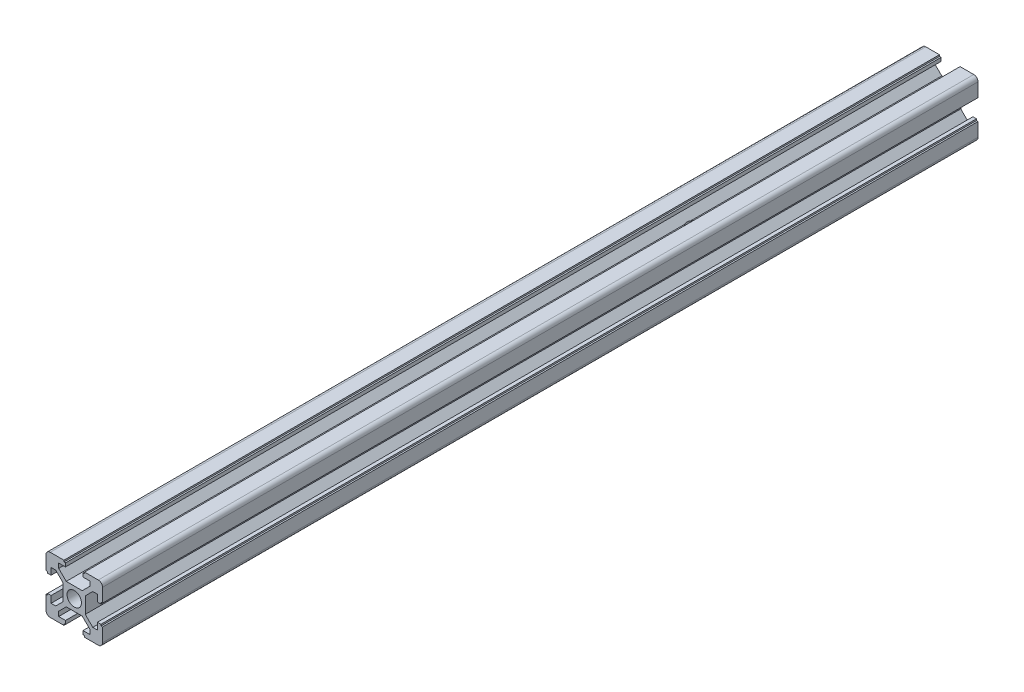
SolidWorks part; units mm, degrees
material "6063-T5"
ref_plane "前视基准面" through (0, 0, 0) normal (0, 0, 1) x (1, 0, 0)
ref_plane "上视基准面" through (0, 0, 0) normal (0, 1, 0) x (1, 0, 0)
ref_plane "右视基准面" through (0, 0, 0) normal (1, 0, 0) x (0, 0, -1)
sketch "草图2" plane through (0, 0, 0) normal (0, 0, 1) x (1, 0, 0)
  line L0 (-3.9, 2.8393) -> (-6.5607, 5.5)
  line L1 (-2.8393, 3.9) -> (2.8393, 3.9)
  line L2 (-3.9, 2.8393) -> (-3.9, -2.8393)
  line L3 (-2.8393, -3.9) -> (2.8393, -3.9)
  line L4 (3.9, 2.8393) -> (3.9, -2.8393)
  line L5 (-3.9, 3.9) -> (3.9, -3.9) construction
  line L6 (-3.9, -3.9) -> (3.9, 3.9) construction
  line L7 (-2.8393, 3.9) -> (-5.5, 6.5607)
  line L8 (-5.5, 6.5607) -> (-5.5, 8.2)
  line L9 (-5.5, 8.2) -> (-3.1, 8.2)
  line L10 (-3.1, 8.2) -> (-3.1, 9.45)
  line L11 (-3.1, 9.45) -> (-3.65, 9.45)
  line L12 (-3.65, 9.45) -> (-3.65, 10)
  line L13 (-3.65, 10) -> (-8.5, 10)
  line L14 (-6.5607, 5.5) -> (-8.2, 5.5)
  line L15 (-10, 3.65) -> (-10, 8.5)
  line L16 (-9.45, 3.65) -> (-10, 3.65)
  line L17 (-9.45, 3.1) -> (-9.45, 3.65)
  line L18 (-8.2, 3.1) -> (-9.45, 3.1)
  line L19 (-8.2, 5.5) -> (-8.2, 3.1)
  line L20 (2.8393, 3.9) -> (5.5, 6.5607)
  line L21 (3.9, 2.8393) -> (6.5607, 5.5)
  line L22 (6.5607, 5.5) -> (8.2, 5.5)
  line L23 (8.2, 5.5) -> (8.2, 3.1)
  line L24 (8.2, 3.1) -> (9.45, 3.1)
  line L25 (9.45, 3.1) -> (9.45, 3.65)
  line L26 (9.45, 3.65) -> (10, 3.65)
  line L27 (10, 3.65) -> (10, 8.5)
  line L28 (5.5, 6.5607) -> (5.5, 8.2)
  line L29 (3.65, 10) -> (8.5, 10)
  line L30 (3.65, 9.45) -> (3.65, 10)
  line L31 (3.1, 9.45) -> (3.65, 9.45)
  line L32 (3.1, 8.2) -> (3.1, 9.45)
  line L33 (5.5, 8.2) -> (3.1, 8.2)
  line L34 (3.9, -2.8393) -> (6.5607, -5.5)
  line L35 (2.8393, -3.9) -> (5.5, -6.5607)
  line L36 (5.5, -6.5607) -> (5.5, -8.2)
  line L37 (5.5, -8.2) -> (3.1, -8.2)
  line L38 (3.1, -8.2) -> (3.1, -9.45)
  line L39 (3.1, -9.45) -> (3.65, -9.45)
  line L40 (3.65, -9.45) -> (3.65, -10)
  line L41 (3.65, -10) -> (8.5, -10)
  line L42 (6.5607, -5.5) -> (8.2, -5.5)
  line L43 (10, -3.65) -> (10, -8.5)
  line L44 (9.45, -3.65) -> (10, -3.65)
  line L45 (9.45, -3.1) -> (9.45, -3.65)
  line L46 (8.2, -3.1) -> (9.45, -3.1)
  line L47 (8.2, -5.5) -> (8.2, -3.1)
  line L48 (-2.8393, -3.9) -> (-5.5, -6.5607)
  line L49 (-3.9, -2.8393) -> (-6.5607, -5.5)
  line L50 (-6.5607, -5.5) -> (-8.2, -5.5)
  line L51 (-8.2, -5.5) -> (-8.2, -3.1)
  line L52 (-8.2, -3.1) -> (-9.45, -3.1)
  line L53 (-9.45, -3.1) -> (-9.45, -3.65)
  line L54 (-9.45, -3.65) -> (-10, -3.65)
  line L55 (-10, -3.65) -> (-10, -8.5)
  line L56 (-5.5, -6.5607) -> (-5.5, -8.2)
  line L57 (-3.65, -10) -> (-8.5, -10)
  line L58 (-3.65, -9.45) -> (-3.65, -10)
  line L59 (-3.1, -9.45) -> (-3.65, -9.45)
  line L60 (-3.1, -8.2) -> (-3.1, -9.45)
  line L61 (-5.5, -8.2) -> (-3.1, -8.2)
  circle A0 centre (0, 0) radius 2.55
  arc A1 (-8.5, 10) -> (-10, 8.5) centre (-8.5, 8.5) ccw
  arc A2 (10, 8.5) -> (8.5, 10) centre (8.5, 8.5) ccw
  arc A3 (8.5, -10) -> (10, -8.5) centre (8.5, -8.5) ccw
  arc A4 (-10, -8.5) -> (-8.5, -10) centre (-8.5, -8.5) ccw
  point P25 (-10, 10)
  point P79 (0, 0)
  dimension "D1" = 5.1
  dimension "D9" = 1.5
  dimension "D2" = 7.8
  dimension "D3" = 1.5
  dimension "D4" = 10
  dimension "D5" = 3.1
  dimension "D6" = 0.55
  dimension "D7" = 1.8
  dimension "D8" = 5.5
  dimension "D11" = 3.9
  dimension "D10" = 4
extrude "凸台-拉伸1" add sketch "草图2" along normal blind 310
sketch "草图3" plane through (0, -10, 0) normal (0, -1, 0) x (1, 0, 0)
  line L0 (200, 90) -> (-43.3624, 90) construction
  circle A0 centre (0, 90) radius 3
  dimension "D1" = 6
extrude "切除-拉伸1" cut sketch "草图3" against normal through all both and the other way through all
